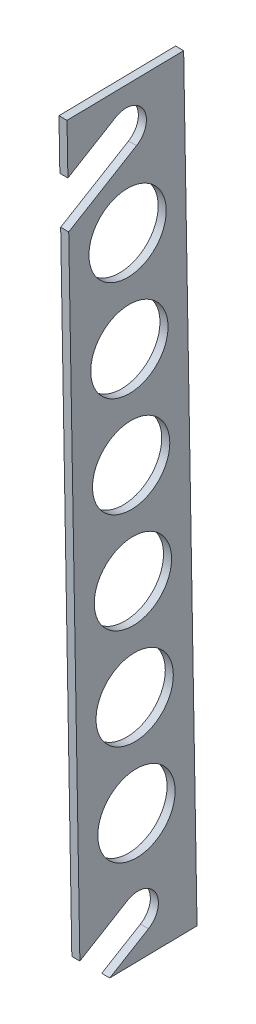
SolidWorks part; units mm, degrees
material "6061-T6 (SS)"
ref_plane "Front" through (0, 0, 0) normal (0, 0, 1) x (1, 0, 0)
ref_plane "Top" through (0, 0, 0) normal (0, 1, 0) x (1, 0, 0)
ref_plane "Right" through (0, 0, 0) normal (1, 0, 0) x (0, 0, -1)
sketch "Sketch1" plane through (0, 0, 0) normal (1, 0, 0) x (0, 0, -1)
  line B0 (-1.1442, 65.3798) -> (-0.6998, 39.9837) construction
  line B1 (1.4941, -85.3717) -> (1.0497, -59.9756) construction
  line B2 (-3.0496, 60.8453) -> (-12.4676, 55.1858) construction
  line B3 (1.0389, 54.0418) -> (-12.3072, 46.0218) construction
  line B4 (-12.6425, 65.1786) -> (-12.4686, 55.2445)
  line B5 (-4.3156, -85.4734) -> (-4.214, -85.4716) construction
  line B6 (12.9924, -85.1704) -> (10.354, 65.5811)
  line B7 (10.354, 65.5811) -> (-12.6425, 65.1786)
  line B8 (-0.689, -74.0336) -> (-10.107, -79.6931) construction
  line B9 (3.3995, -80.8372) -> (-4.3156, -85.4734) construction
  line B10 (-12.3072, 46.0218) -> (-12.3062, 45.9631) construction
  line B11 (1.065, 53.9982) -> (-12.3062, 45.9631)
  line B12 (-3.0757, 60.8889) -> (-12.4686, 55.2445)
  line B13 (-12.3062, 45.9631) -> (-10.108, -79.6345)
  line B14 (-12.4686, 55.2445) -> (-12.4676, 55.1858) construction
  line B15 (3.4256, -80.8807) -> (-4.214, -85.4716)
  line B16 (-0.7151, -73.9901) -> (-10.108, -79.6345)
  line B17 (-10.108, -79.6345) -> (-10.107, -79.6931) construction
  line B18 (-4.214, -85.4716) -> (12.9924, -85.1704)
  arc B19 (3.3995, -80.8372) -> (-0.689, -74.0336) centre (1.3552, -77.4354) ccw construction
  arc B20 (1.0389, 54.0418) -> (-3.0496, 60.8453) centre (-1.0054, 57.4435) ccw construction
  circle B21 centre (-0.6998, 39.9837) radius 7.62
  circle B22 centre (-0.3499, 19.9919) radius 7.62
  circle B23 centre (0, 0) radius 7.62
  circle B24 centre (0.3499, -19.9919) radius 7.62
  circle B25 centre (0.6998, -39.9837) radius 7.62
  circle B26 centre (1.0497, -59.9756) radius 7.62
  arc B27 (1.065, 53.9982) -> (-3.0757, 60.8889) centre (-1.0054, 57.4435) ccw
  arc B28 (3.4256, -80.8807) -> (-0.7151, -73.9901) centre (1.3552, -77.4354) ccw
sketch_block_instance "Block1-1"
sketch_block "Block1" parameters "D1"=7.62, "D2"=25.4, "D3"=30
extrude "Boss-Extrude1" add sketch "Sketch1" along normal blind 1.5875
